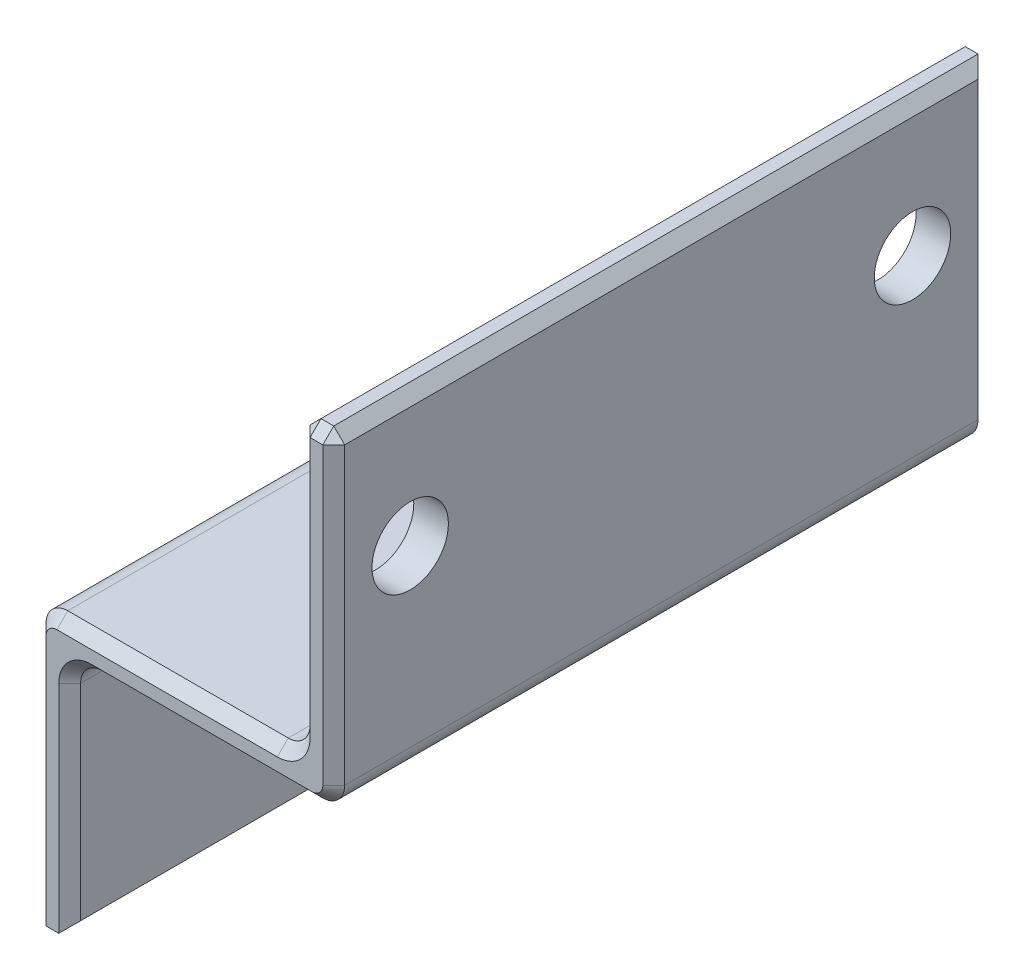
SolidWorks part; units mm, degrees
ref_plane "Alzado" through (0, 0, 0) normal (0, 0, 1) x (1, 0, 0)
ref_plane "Planta" through (0, 0, 0) normal (0, 1, 0) x (1, 0, 0)
ref_plane "Vista lateral" through (0, 0, 0) normal (1, 0, 0) x (0, 0, -1)
sketch "Croquis1" plane through (0, 0, 0) normal (0, 0, 1) x (1, 0, 0)
  line L0 (-16.0312, -21.0155) -> (-16.0312, 0.8145)
  line L1 (-16.0312, 0.8145) -> (8.1488, 0.8145)
  line L2 (8.1488, 0.8145) -> (8.1488, 30.8145)
  line L3 (8.1488, 30.8145) -> (4.9788, 30.8145)
  line L4 (4.9788, 30.8145) -> (4.9788, 3.9845)
  line L5 (4.9788, 3.9845) -> (-19.2012, 3.9845)
  line L6 (-19.2012, 3.9845) -> (-19.2012, -21.0155)
  line L7 (-19.2012, -21.0155) -> (-16.0312, -21.0155)
  dimension "D1" = 3.17
  dimension "D2" = 3.17
  dimension "D3" = 3.17
  dimension "D4" = 27.35
  dimension "D5" = 25
  dimension "D6" = 30
extrude "Saliente-Extruir1" add sketch "Croquis1" along normal blind 60
fillet "Redondeo1" radius 2 4 edges at (-19.2012, 3.9845, 30) (4.9788, 3.9845, 30) (8.1488, 0.8145, 30) (-16.0312, 0.8145, 30)
sketch "Croquis2" plane through (8.1488, 0, 0) normal (1, 0, 0) x (0, 0, -1)
  line L0 (-60, 7.1645) -> (0, 7.1645) construction
  line L1 (-60, 2.8145) -> (-60, 30.8145) construction
  line L2 (0, 2.8145) -> (0, 30.8145) construction
  line L3 (-60, 0.8145) -> (0, 0.8145) construction
  line L4 (-53, 18.8145) -> (-53, 30.8145) construction
  line L5 (-60, 30.8145) -> (0, 30.8145) construction
  line L6 (-49.5, 18.8145) -> (-53, 18.8145) construction
  circle A0 centre (-53, 18.8145) radius 3.5
  circle A1 centre (-7, 18.8145) radius 3.5
  point P11 (-30, 20.8145)
  dimension "D4" = 7
  dimension "D5" = 7
  dimension "D1" = 6.35
  dimension "D2" = 10
  dimension "D3" = 12
  dimension "D6" = 12
extrude "Cortar-Extruir1" cut sketch "Croquis2" against normal blind 60
chamfer "Chaflán1" distance 1 angle 45 25 edges at (-16.0312, -21.0155, 30) (-19.2012, -21.0155, 30) (-16.0312, -11.1005, 60) (-19.2012, -9.5155, 60) (-19.2012, -9.5155, 0) (-16.0312, -11.1005, 0) (-15.4454, 0.2287, 60) (-18.6154, 3.3987, 60) (-18.6154, 3.3987, 0) (-15.4454, 0.2287, 0) (-3.9412, 0.8145, 60) (-7.1112, 3.9845, 60) (-7.1112, 3.9845, 0) (-3.9412, 0.8145, 0) (7.563, 1.4003, 60) (4.393, 4.5703, 60) (4.393, 4.5703, 0) (7.563, 1.4003, 0) (8.1488, 16.8145, 60) (4.9788, 18.3995, 60) (4.9788, 18.3995, 0) (8.1488, 16.8145, 0) (8.1488, 30.8145, 30) (4.9788, 30.8145, 30) (6.5638, 30.8145, 60)
